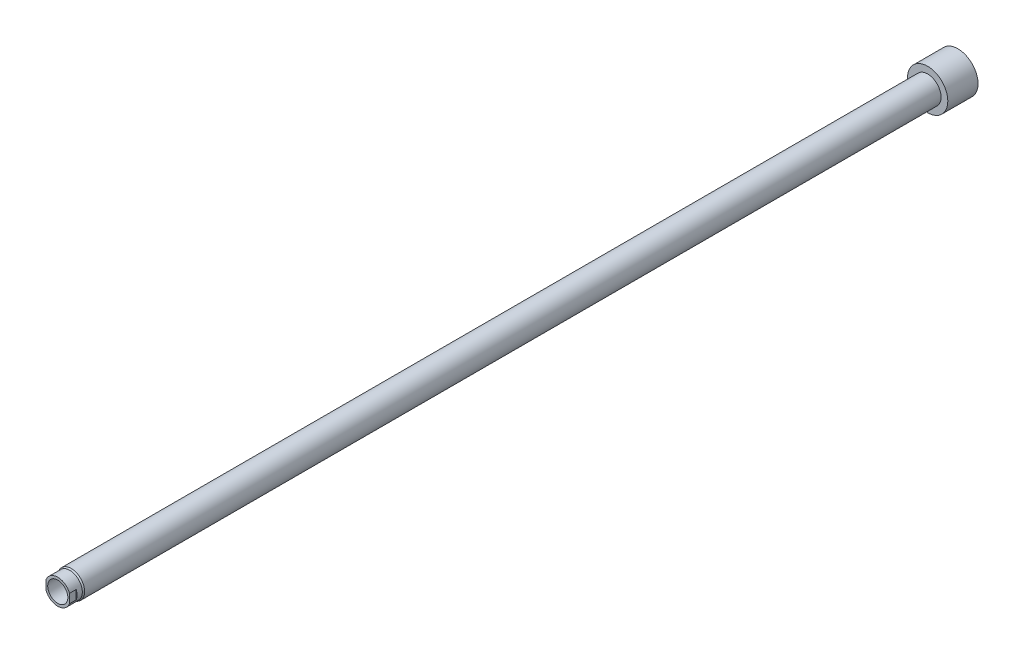
SolidWorks part; units mm, degrees
ref_plane "Front Plane" through (0, 0, 0) normal (0, 0, 1) x (1, 0, 0)
ref_plane "Top Plane" through (0, 0, 0) normal (0, 1, 0) x (1, 0, 0)
ref_plane "Right Plane" through (0, 0, 0) normal (1, 0, 0) x (0, 0, -1)
ref_plane "Plane1" through (0, 0, 0) normal (0, -1, 0) x (1, 0, 0)
sketch "Sketch1" plane through (0, 0, 0) normal (0, -1, 0) x (1, 0, 0)
  line L0 (19.05, -657.225) -> (0, -657.225)
  line L1 (0, -657.225) -> (0, -685.8)
  line L2 (0, -685.8) -> (19.05, -685.8)
  line L3 (19.05, -685.8) -> (19.05, -657.225)
  line L4 (0, -657.225) -> (0, -685.8) construction
revolve "Revolve1" add sketch "Sketch1" angle 360 about L4
sketch "Sketch2" plane through (0, 0, -657.225) normal (0, 0, 1) x (1, 0, 0)
  circle A0 centre (0, 0) radius 12.7
extrude "Boss-Extrude1" add sketch "Sketch2" along normal blind 695.325
sketch "Sketch3" plane through (0, 0, 38.1) normal (0, 0, 1) x (1, 0, 0)
  circle A0 centre (0, 0) radius 12.7
extrude "Boss-Extrude2" add sketch "Sketch3" along normal blind 1.3748 draft 30
sketch "Sketch4" plane through (0, 0, 39.4748) normal (0, 0, 1) x (1, 0, 0)
  circle A0 centre (0, 0) radius 11.9062
extrude "Boss-Extrude3" add sketch "Sketch4" along normal blind 11.3252
sketch "Sketch5" plane through (0, 0, 50.8) normal (0, 0, 1) x (1, 0, 0)
  line L0 (11.1125, 4.2745) -> (11.1125, -4.2745)
  arc A0 (11.1125, -4.2745) -> (11.1125, 4.2745) centre (0, 0) ccw
extrude "Cut-Extrude1" cut sketch "Sketch5" against normal blind 6.35
sketch "Sketch6" plane through (0, 0, 50.8) normal (0, 0, 1) x (1, 0, 0)
  line L0 (-11.1125, -4.2745) -> (-11.1125, 4.2745)
  arc A0 (-11.1125, 4.2745) -> (-11.1125, -4.2745) centre (0, 0) ccw
extrude "Cut-Extrude2" cut sketch "Sketch6" against normal blind 6.35
sketch "Sketch10" plane through (0, 0, 50.8) normal (0, 0, 1) x (1, 0, 0)
  circle A0 centre (0, 0) radius 9.525
  dimension "D1" = 19.05
extrude "Cut-Extrude4" cut sketch "Sketch10" against normal blind 28.575
sketch "Sketch8" plane through (0, 0, -685.8) normal (0, 0, -1) x (-1, 0, 0)
  circle A0 centre (0, 0) radius 19.05
extrude "Boss-Extrude5" add sketch "Sketch8" along normal blind 114.3
sketch "Sketch9" plane through (0, 0, -657.225) normal (0, 0, 1) x (1, 0, 0)
  circle A0 centre (0, 0) radius 19.05
  circle A1 centre (0, 0) radius 12.7
extrude "Cut-Extrude3" cut sketch "Sketch9" against normal blind 114.3
